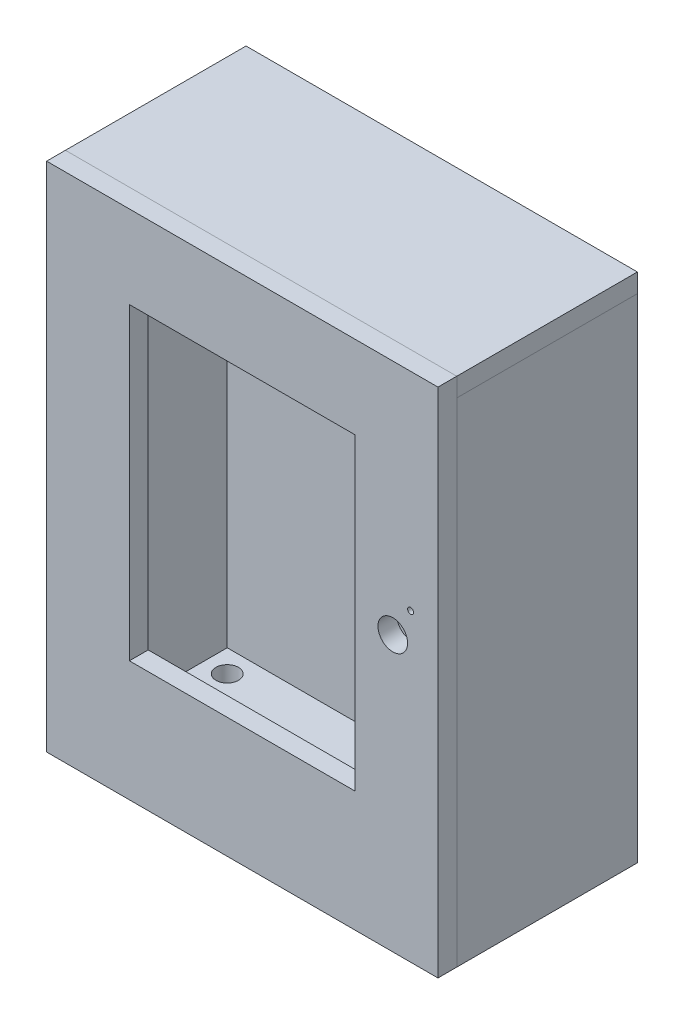
SolidWorks part; units mm, degrees
ref_plane "Default Plane" through (139.7, 34.925, -144.4625) normal (0, 0, -1) x (-1, 0, 0)
sketch3d "Bounding-Box_Cut-List-Item1"
  line L0 (279.4, -15.875, 0) -> (0, -15.875, 0) construction
  line L1 (0, -15.875, 0) -> (0, 60.325, 0) construction
  line L2 (0, 60.325, 0) -> (279.4, 60.325, 0) construction
  line L3 (279.4, 60.325, 0) -> (279.4, -15.875, 0) construction
  line L4 (279.4, -15.875, 15.875) -> (0, -15.875, 15.875) construction
  line L5 (0, -15.875, 15.875) -> (0, 60.325, 15.875) construction
  line L6 (0, 60.325, 15.875) -> (279.4, 60.325, 15.875) construction
  line L7 (279.4, 60.325, 15.875) -> (279.4, -15.875, 15.875) construction
  line L8 (279.4, -15.875, 0) -> (279.4, -15.875, 15.875) construction
  line L9 (0, -15.875, 0) -> (0, -15.875, 15.875) construction
  line L10 (0, 60.325, 0) -> (0, 60.325, 15.875) construction
  line L11 (279.4, 60.325, 0) -> (279.4, 60.325, 15.875) construction
other "Markup2"
sketch "Sketch17" plane through (-171.45, -231.775, 7.9375) normal (0, 0, 1) x (1, 0, 0)
ref_plane "Front Plane" through (0, 0, 0) normal (0, 0, 1) x (1, 0, 0)
ref_plane "Top Plane" through (0, 0, 0) normal (0, 1, 0) x (1, 0, 0)
ref_plane "Right Plane" through (0, 0, 0) normal (1, 0, 0) x (0, 0, -1)
sketch "Sketch1" plane through (0, 0, 0) normal (0, 0, 1) x (1, 0, 0)
  line L0 (-165.1, 200.025) -> (165.1, 200.025)
  line L1 (-95.25, -130.175) -> (95.25, -130.175)
  line L2 (-95.25, -130.175) -> (-95.25, 130.175)
  line L3 (-95.25, 130.175) -> (95.25, 130.175)
  line L4 (95.25, -130.175) -> (95.25, 130.175)
  line L5 (-95.25, -130.175) -> (95.25, 130.175) construction
  line L6 (-95.25, 130.175) -> (95.25, -130.175) construction
  line L7 (165.1, -231.775) -> (165.1, 200.025)
  line L8 (-165.1, -231.775) -> (165.1, -231.775)
  line L9 (-165.1, -231.775) -> (-165.1, 200.025)
  circle A0 centre (127, 0) radius 12.5
  circle A1 centre (142, 25) radius 2.5
  point P0 (0, 0)
  dimension "D5" = 25
  dimension "D8" = 5
  dimension "D1" = 190.5
  dimension "D2" = 260.35
  dimension "D4" = 38.1
  dimension "D6" = 25
  dimension "D7" = 15
  dimension "D3" = 69.85
  dimension "D9" = 101.6
  dimension "D10" = 69.85
  dimension "D11" = 69.85
extrude "Boss-Extrude1" add sketch "Sketch1" along normal mid plane 15.875
sketch "Sketch3" plane through (165.1, 0, 0) normal (1, 0, 0) x (0, 0, -1)
  line L0 (-7.9375, -231.775) -> (7.9375, -231.775) construction
  line L1 (7.9375, 184.15) -> (160.3375, 184.15)
  line L2 (7.9375, 184.15) -> (7.9375, -231.775)
  line L3 (7.9375, -231.775) -> (160.3375, -231.775)
  line L4 (160.3375, 184.15) -> (160.3375, -231.775)
  line L5 (7.9375, 184.15) -> (160.3375, -231.775) construction
  line L6 (7.9375, -231.775) -> (160.3375, 184.15) construction
  line L7 (7.9375, -231.775) -> (7.9375, 200.025) construction
  line L8 (-7.9375, -231.775) -> (-7.9375, 200.025) construction
  line L10 (-7.9375, 200.025) -> (7.9375, 200.025) construction
  point P4 (84.1375, -23.8125)
  dimension "D1" = 168.275
  dimension "D2" = 152.4
  dimension "D3" = 15.875
extrude "Boss-Extrude2" add sketch "Sketch3" against normal blind 15.875 separate body
mirror "Mirror1" about plane through (0, 0, 0) normal (1, 0, 0) of bodies 102
sketch "Sketch8" plane through (0, 0, -160.3375) normal (0, 0, -1) x (-1, 0, 0)
  line L0 (-149.225, -231.775) -> (-149.225, 184.15) construction
  line L1 (-149.225, 184.15) -> (149.225, 184.15)
  line L2 (-149.225, 184.15) -> (-149.225, -231.775)
  line L3 (-149.225, -231.775) -> (149.225, -231.775)
  line L4 (149.225, 184.15) -> (149.225, -231.775)
  line L5 (-149.225, 184.15) -> (149.225, -231.775) construction
  line L6 (-149.225, -231.775) -> (149.225, 184.15) construction
  line L7 (-165.1, 200.025) -> (165.1, 200.025) construction
  point P4 (0, -23.8125)
  point P7 (-155.575, 231.775)
  point P9 (155.575, -231.775)
  point P11 (-148.5868, 190.1495)
  point P14 (-155.575, 191.8855)
  dimension "D1" = 15.875
extrude "Boss-Extrude6" add sketch "Sketch8" against normal blind 15.875 from offset 15.875 separate body offset against normal yes
sketch "Sketch11" plane through (0, -231.775, 0) normal (0, -1, 0) x (1, 0, 0)
  line L0 (-149.225, -7.9375) -> (-149.225, -160.3375) construction
  line L1 (-149.225, -7.9375) -> (149.225, -7.9375)
  line L2 (-149.225, -7.9375) -> (-149.225, -128.5875)
  line L3 (-149.225, -128.5875) -> (149.225, -128.5875)
  line L4 (149.225, -7.9375) -> (149.225, -128.5875)
  line L5 (-149.225, -7.9375) -> (149.225, -128.5875) construction
  line L6 (-149.225, -128.5875) -> (149.225, -7.9375) construction
  line L7 (-165.1, -7.9375) -> (165.1, -7.9375) construction
  circle A0 centre (-130.175, -109.5375) radius 9.525
  point P4 (0, -68.2625)
  point P9 (-155.575, -7.9375)
  point P12 (-155.575, -7.9375)
  point P15 (155.575, -128.5875)
  dimension "D1" = 19.05
  dimension "D2" = 19.05
  dimension "D3" = 19.05
extrude "Boss-Extrude7" add sketch "Sketch11" against normal blind 15.875 separate body
sketch "Sketch14" plane through (0, 200.025, 0) normal (0, 1, 0) x (1, 0, 0)
  line L0 (149.225, 7.9375) -> (-149.225, 7.9375) construction
  line L1 (-165.1, 160.3375) -> (165.1, 160.3375)
  line L2 (-165.1, 160.3375) -> (-165.1, 7.9375)
  line L3 (-165.1, 7.9375) -> (165.1, 7.9375)
  line L4 (165.1, 160.3375) -> (165.1, 7.9375)
  line L5 (-165.1, 160.3375) -> (165.1, 7.9375) construction
  line L6 (-165.1, 7.9375) -> (165.1, 160.3375) construction
  line L7 (165.1, 160.3375) -> (165.1, 7.9375) construction
  point P4 (0, 84.1375)
extrude "Boss-Extrude8" add sketch "Sketch14" against normal blind 15.875 separate body
sketch "Sketch7" plane through (0, 0, 0) normal (1, 0, 0) x (0, 0, -1)
  line L0 (144.4625, 95.25) -> (144.4625, 34.925)
  line L2 (144.4625, 34.925) -> (160.3375, 19.05)
  line L3 (160.3375, 19.05) -> (160.3375, 95.25)
  line L4 (160.3375, 95.25) -> (144.4625, 95.25)
  line L6 (160.3375, -82.55) -> (144.4625, -82.55)
  line L7 (144.4625, -82.55) -> (144.4625, -142.875)
  line L8 (144.4625, -142.875) -> (160.3375, -158.75)
  line L9 (160.3375, -158.75) -> (160.3375, -82.55)
  line L11 (160.3375, 184.15) -> (7.9375, 184.15) construction
  line L12 (7.9375, -231.775) -> (160.3375, -231.775) construction
  line L13 (144.4625, 184.15) -> (144.4625, -231.775) construction
  dimension "D1" = 76.2
  dimension "D2" = 15.875
  dimension "D3" = 45
  dimension "D4" = 88.9
  dimension "D6" = 177.8
  dimension "D7" = 73.025
  dimension "D5" = 2
extrude "Boss-Extrude5" add sketch "Sketch7" along normal mid plane 279.4 separate body
